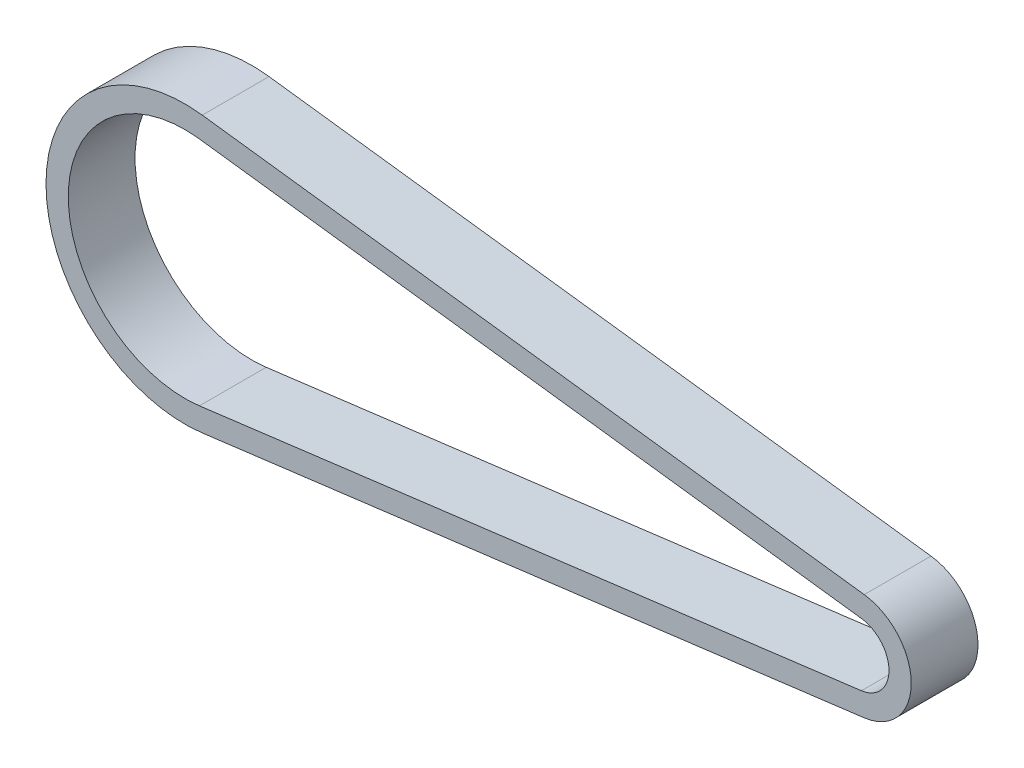
SolidWorks part; units mm, degrees
material "NEOPRENE"
ref_plane "Plano frontal" through (0, 0, 0) normal (0, 0, 1) x (1, 0, 0)
ref_plane "Plano superior" through (0, 0, 0) normal (0, 1, 0) x (1, 0, 0)
ref_plane "Plano direito" through (0, 0, 0) normal (1, 0, 0) x (0, 0, -1)
sketch "Esboço1" plane through (0, 0, 0) normal (0, 0, 1) x (1, 0, 0)
  line L0 (2.1719, 17.0623) -> (91.4021, 5.704) construction
  line L1 (91.4021, -5.704) -> (2.1719, -17.0623) construction
  line L2 (1.9825, 15.5743) -> (91.2127, 4.216)
  line L3 (91.2127, -4.216) -> (1.9825, -15.5743)
  line L4 (2.3613, 18.5503) -> (91.5915, 7.192)
  line L5 (91.5915, -7.192) -> (2.3613, -18.5503)
  circle A6 centre (0, 0) radius 17.2 construction
  circle A7 centre (90.676, 0) radius 5.75 construction
  circle A8 centre (0, 0) radius 18.7
  circle A9 centre (90.676, 0) radius 7.25
  circle A10 centre (0, 0) radius 15.7
  circle A11 centre (90.676, 0) radius 4.25
  dimension "D1" = 34.4
  dimension "D5" = 1.5
  dimension "D3" = 11.5
  dimension "D2" = 90.676
  dimension "D4" = 1.5
extrude "Ressalto-extrusão1" add sketch "Esboço1" along normal mid plane 9 contours A11 L3 A9 L2 | A9 L3 A8 L5 | A9 L4 A8 L2 | A10 L2 A8 L3
